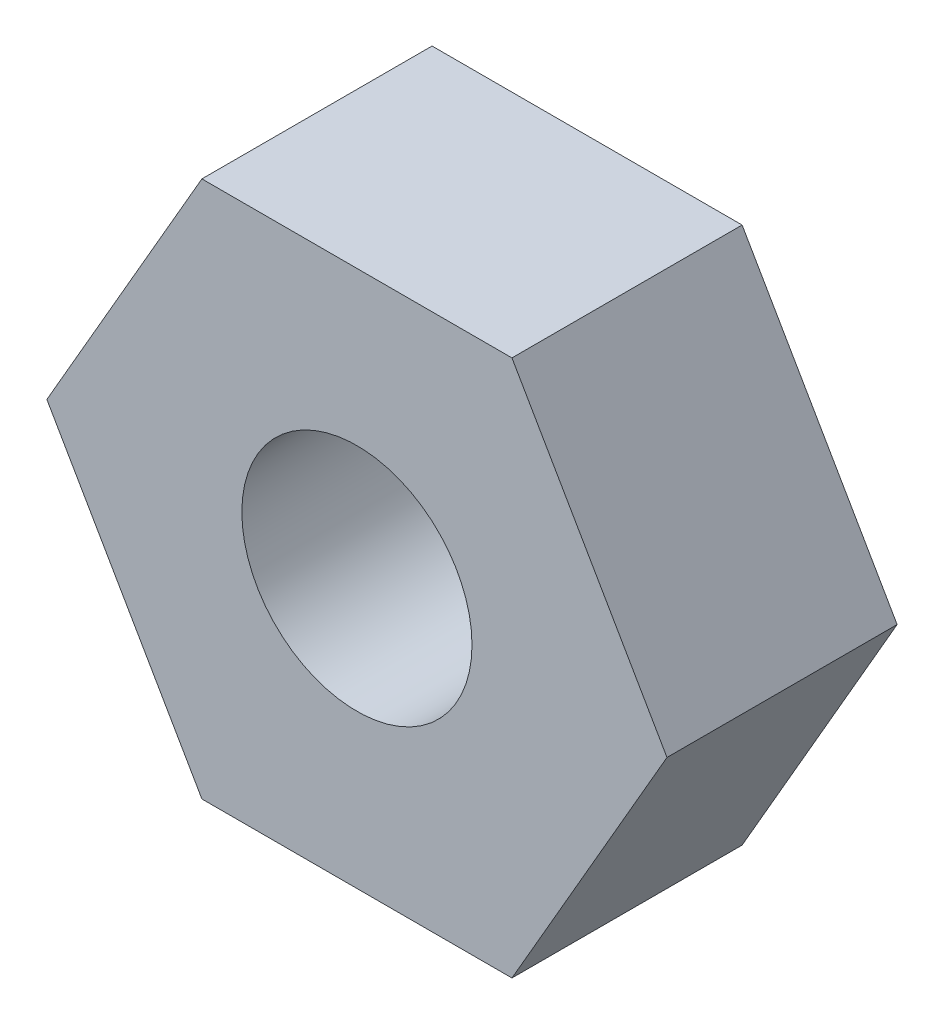
SolidWorks part; units mm, degrees
ref_plane "Front Plane" through (0, 0, 0) normal (0, 0, 1) x (1, 0, 0)
ref_plane "Top Plane" through (0, 0, 0) normal (0, 1, 0) x (1, 0, 0)
ref_plane "Right Plane" through (0, 0, 0) normal (1, 0, 0) x (0, 0, -1)
sketch "Sketch1" plane through (0, 0, 0) normal (0, 0, 1) x (1, 0, 0)
  line L1 (-4.0415, 0) -> (-2.0207, -3.5)
  line L2 (-2.0207, -3.5) -> (2.0207, -3.5)
  line L3 (2.0207, -3.5) -> (4.0415, 0)
  line L4 (4.0415, 0) -> (2.0207, 3.5)
  line L5 (2.0207, 3.5) -> (-2.0207, 3.5)
  line L6 (-2.0207, 3.5) -> (-4.0415, 0)
  circle A0 centre (0, 0) radius 1.5
  circle A2 centre (0, 0) radius 3.5 construction
  dimension "D1" = 3
  dimension "D2" = 7
extrude "Boss-Extrude1" add sketch "Sketch1" along normal blind 3
